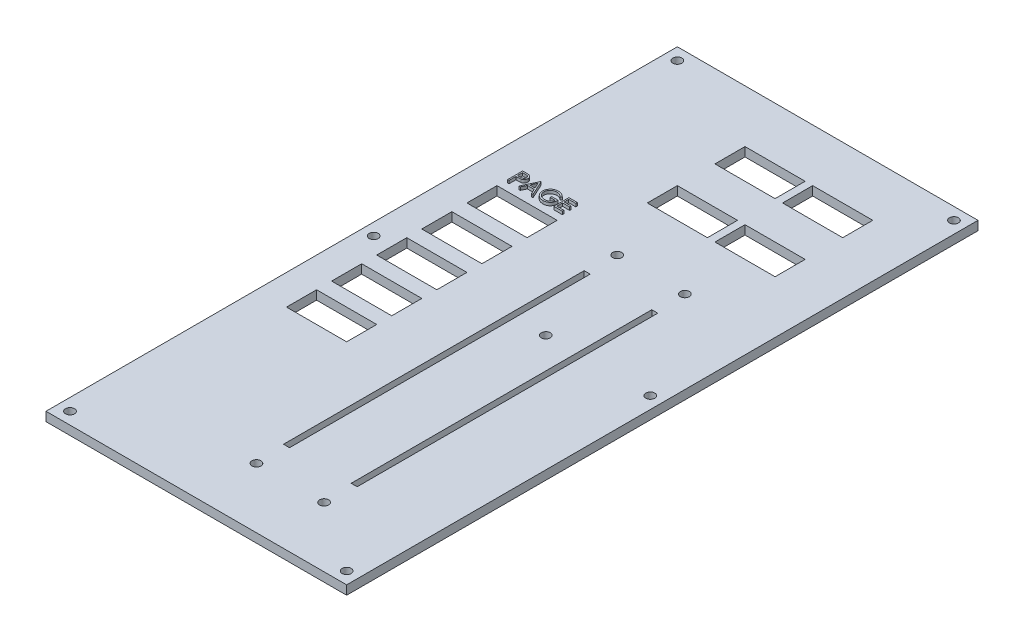
SolidWorks part; units mm, degrees
ref_plane "Front Plane" through (0, 0, 0) normal (0, 0, 1) x (1, 0, 0)
ref_plane "Top Plane" through (0, 0, 0) normal (0, 1, 0) x (1, 0, 0)
ref_plane "Right Plane" through (0, 0, 0) normal (1, 0, 0) x (0, 0, -1)
sketch "Sketch1" plane through (0, 0, 0) normal (0, 1, 0) x (1, 0, 0)
  line L1 (-50, -105) -> (50, -105)
  line L2 (-50, -105) -> (-50, 105)
  line L3 (-50, 105) -> (50, 105)
  line L4 (50, -105) -> (50, 105)
  line L5 (-50, -105) -> (50, 105) construction
  line L6 (-50, 105) -> (50, -105) construction
  point P0 (0, 0)
  dimension "D1" = 210
  dimension "D2" = 100
extrude "Boss-Extrude1" add sketch "Sketch1" along normal blind 3 contours L2 L3 L4 L1
sketch "Sketch3" plane through (0, 3, 0) normal (0, 1, 0) x (1, 0, 0)
  line L0 (-1, 25) -> (1, 25)
  line L1 (-1, 25) -> (-1, -75)
  line L2 (-1, -75) -> (1, -75)
  line L3 (1, 25) -> (1, -75)
  line L4 (-1, 25) -> (1, -75) construction
  line L5 (-1, -75) -> (1, 25) construction
  line L6 (-50, -105) -> (-50, 105) construction
  circle A0 centre (0, -85) radius 1.5
  circle A1 centre (0, 35) radius 1.5
  point P0 (0, -25)
  dimension "D3" = 3
  dimension "D4" = 3
  dimension "D1" = 100
  dimension "D2" = 2
  dimension "D5" = 120
  dimension "D6" = 60
  dimension "D7" = 50
  dimension "D8" = 25
extrude "Cut-Extrude1" cut sketch "Sketch3" against normal up to next
pattern_linear "LPattern1" count 2 spacing 22.5 along (1, 0, 0) of "Cut-Extrude1"
sketch "Sketch4" plane through (0, 3, 0) normal (0, 1, 0) x (1, 0, 0)
  line L1 (-10, 55) -> (10, 55)
  line L2 (-10, 55) -> (-10, 65)
  line L3 (-10, 65) -> (10, 65)
  line L4 (10, 55) -> (10, 65)
  line L5 (-10, 55) -> (10, 65) construction
  line L6 (-10, 65) -> (10, 55) construction
  circle A0 centre (0, 35) radius 1.5 construction
  point P0 (0, 60)
  dimension "D1" = 10
  dimension "D2" = 20
  dimension "D3" = 25
extrude "Cut-Extrude2" cut sketch "Sketch4" against normal up to next
pattern_linear "LPattern2" count 2 spacing 22.5 along (1, 0, 0) count 2 spacing 22.5 along (0, 0, -1) of "Cut-Extrude2"
sketch "Sketch5" plane through (0, 3, 0) normal (0, 1, 0) x (1, 0, 0)
  line L0 (-50, 105) -> (50, 105) construction
  line L1 (-50, -105) -> (-50, 105) construction
  line L2 (50, -105) -> (50, 105) construction
  line L3 (-50, -105) -> (50, -105) construction
  circle A0 centre (-46, 101) radius 1.5
  circle A1 centre (46, 101) radius 1.5
  circle A2 centre (46, -101) radius 1.5
  circle A3 centre (-46, -101) radius 1.5
  circle A4 centre (11.25, 0) radius 1.5
  dimension "D1" = 3
  dimension "D4" = 3
  dimension "D9" = 3
  dimension "D10" = 3
  dimension "D13" = 3
  dimension "D2" = 4
  dimension "D3" = 4
  dimension "D5" = 4
  dimension "D6" = 4
  dimension "D7" = 4
  dimension "D8" = 4
  dimension "D11" = 4
  dimension "D12" = 4
  dimension "D14" = 11.25
extrude "Cut-Extrude3" cut sketch "Sketch5" against normal up to next
sketch "Sketch6" plane through (0, 3, 0) normal (0, 1, 0) x (1, 0, 0)
  line L0 (-50, -105) -> (-50, 105) construction
  line L1 (-40, 35) -> (-20, 35)
  line L2 (-40, 35) -> (-40, 25)
  line L3 (-40, 25) -> (-20, 25)
  line L4 (-20, 35) -> (-20, 25)
  line L5 (-40, 35) -> (-20, 25) construction
  line L6 (-40, 25) -> (-20, 35) construction
  point P0 (-30, 30)
  dimension "D1" = 20
  dimension "D2" = 10
  dimension "D3" = 20
  dimension "D4" = 30
extrude "Cut-Extrude4" cut sketch "Sketch6" against normal up to next
pattern_linear "LPattern3" count 5 spacing 15 along (0, 0, 1) of "Cut-Extrude4"
sketch "Sketch7" plane through (0, 3, 0) normal (0, 1, 0) x (1, 0, 0)
  line L0 (-50, -105) -> (-50, 105) construction
  circle A0 centre (-46, 0) radius 1.5
  dimension "D1" = 3
  dimension "D2" = 4
extrude "Cut-Extrude5" cut sketch "Sketch7" against normal up to next
sketch "Sketch8" plane through (0, 3, 0) normal (0, 1, 0) x (1, 0, 0)
  line L0 (50, -105) -> (50, 105) construction
  circle A0 centre (46, 0) radius 1.5
  dimension "D1" = 3
  dimension "D2" = 4
extrude "Cut-Extrude6" cut sketch "Sketch8" against normal up to next
sketch "Sketch10" plane through (0, 3, 0) normal (0, 1, 0) x (1, 0, 0)
  text T0 "PAGE" font "Century Gothic" height 5
  dimension "D1" = 0.4
  dimension "D2" = 2.5
extrude "Boss-Extrude2" add sketch "Sketch10" along normal blind 1
